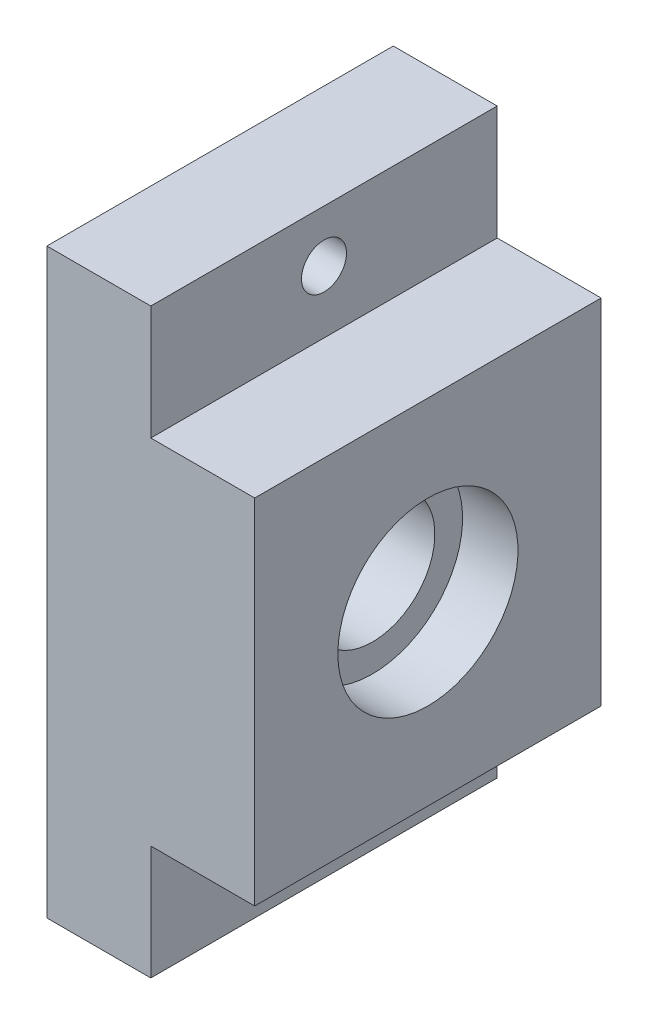
SolidWorks part; units mm, degrees
ref_plane "Front" through (0, 0, 0) normal (0, 0, 1) x (1, 0, 0)
ref_plane "Top" through (0, 0, 0) normal (0, 1, 0) x (1, 0, 0)
ref_plane "Right" through (0, 0, 0) normal (1, 0, 0) x (0, 0, -1)
sketch "Sketch1" plane through (0, 0, 0) normal (0, 0, 1) x (1, 0, 0)
  line L0 (0, 42) -> (0, -42)
  line L1 (0, -42) -> (15, -42)
  line L2 (15, -42) -> (15, -25.5)
  line L3 (15, -25.5) -> (30, -25.5)
  line L4 (30, -25.5) -> (30, 25.5)
  line L5 (30, 25.5) -> (15, 25.5)
  line L6 (15, 25.5) -> (15, 42)
  line L7 (15, 42) -> (0, 42)
  line L8 (-7.604, 0) -> (34.73, 0) construction
  dimension "D1" = 84
  dimension "D2" = 15
  dimension "D3" = 15
  dimension "D4" = 51
extrude "Boss-Extrude1" add sketch "Sketch1" along normal blind 50
hole_wizard "Ø6.5 (6.5) Diameter Hole1" positions "Sketch3" profile "Sketch2" hole size "Ø6.5" standard "ISO" end condition through all
sketch "Sketch3" plane through (15, 0, 0) normal (1, 0, 0) x (0, 0, -1)
  line L0 (0, 0) -> (-50, 0) construction
  line L1 (-50, -25.5) -> (-50, 25.5) construction
  line L3 (0, -25.5) -> (0, 25.5) construction
  point P0 (-25, -34.5)
  point P1 (-25, 34.5)
  dimension "D1" = 25
  dimension "D2" = 69
sketch "Sketch2" plane through (15, -34.5, 25) normal (0, 1, 0) x (0, 0, -1)
  line L0 (0, 0) -> (0, 15)
  line L1 (0, 15) -> (3.25, 15)
  line L2 (3.25, 15) -> (3.25, 0)
  line L5 (3.25, 0) -> (0, 0)
  line L11 (0, -6.35) -> (0, 107.95) construction
  dimension "Thru Hole Dia." = 6.5
  dimension "Thru Hole Depth" = 15
sketch "Sketch4" plane through (0, 0, 0) normal (0, 1, 0) x (1, 0, 0)
  line L0 (0, -25) -> (0, -38)
  line L1 (0, -50) -> (0, 0) construction
  line L2 (0, -38) -> (8, -38)
  line L3 (8, -38) -> (8, -34)
  line L4 (8, -34) -> (22, -34)
  line L5 (22, -34) -> (22, -38)
  line L6 (22, -38) -> (30, -38)
  line L7 (30, -50) -> (30, 0) construction
  line L8 (30, -38) -> (30, -25)
  line L9 (30, -25) -> (0, -25)
  line L10 (0, -25) -> (44.2032, -25) construction
  dimension "D1" = 26
  dimension "D2" = 18
  dimension "D3" = 14
revolve "Cut-Revolve1" cut sketch "Sketch4" angle 360 about L10
